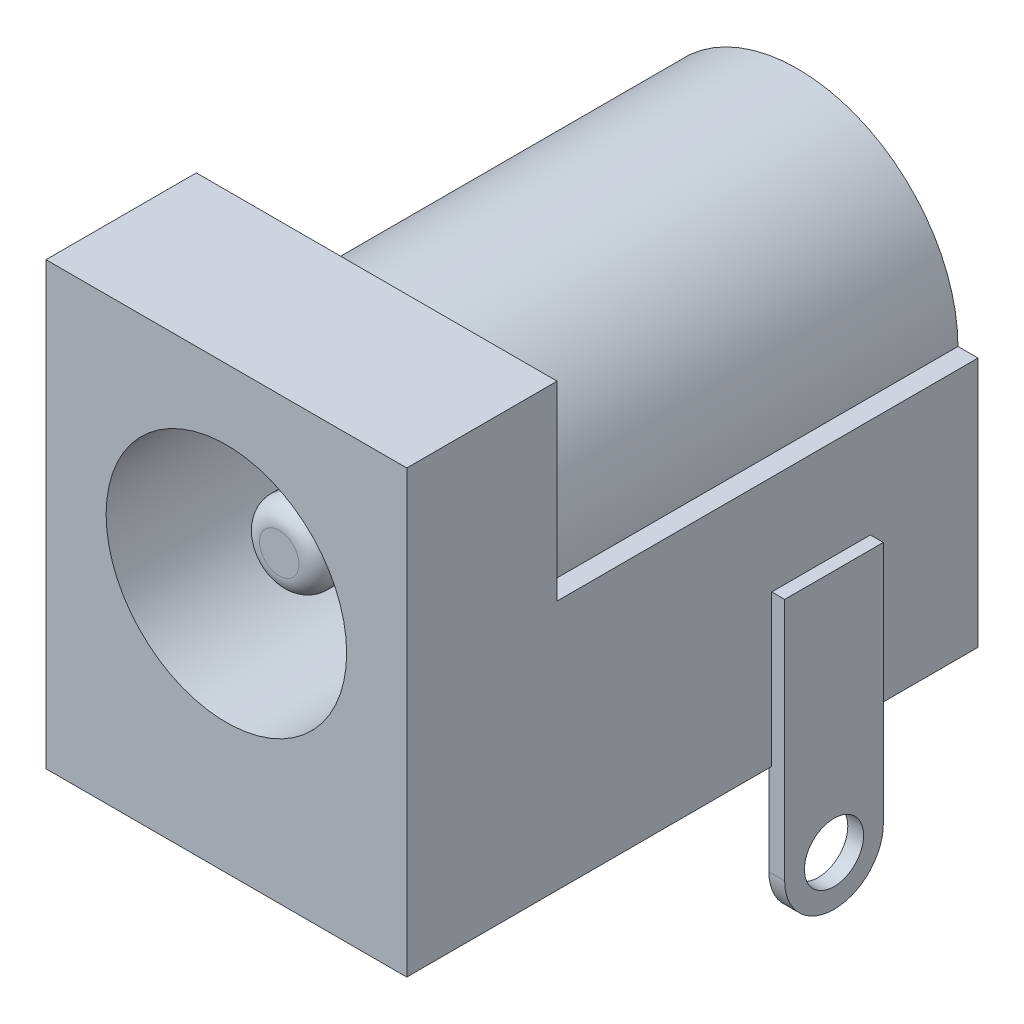
SolidWorks part; units mm, degrees
ref_plane "Plane1" through (0, 0, 0) normal (0, 0, 1) x (1, 0, 0)
ref_plane "Plane2" through (0, 0, 0) normal (0, 1, 0) x (1, 0, 0)
ref_plane "Plane3" through (0, 0, 0) normal (1, 0, 0) x (0, 0, -1)
sketch "Sketch1" plane through (0, 0, 0) normal (0, 0, 1) x (1, 0, 0)
  line L1 (-4.572, 0) -> (4.572, 0)
  line L2 (-4.572, 0) -> (-4.572, 11.176)
  line L3 (-4.572, 11.176) -> (4.572, 11.176)
  line L4 (4.572, 0) -> (4.572, 11.176)
  dimension "D1" = 9.144
  dimension "D2" = 11.176
extrude "Base-Extrude" add sketch "Sketch1" against normal blind 3.81
sketch "Sketch2" plane through (0, 0, -3.81) normal (0, 0, -1) x (-1, 0, 0)
  line L0 (4.572, 0) -> (-4.572, 0) construction
  line L1 (-4.572, 0) -> (-4.572, 11.176) construction
  line L2 (4.572, 11.176) -> (4.572, 0) construction
  line L3 (-4.572, 0) -> (-4.572, 6.35)
  line L4 (4.572, 0) -> (-4.572, 0)
  line L5 (4.572, 6.35) -> (4.572, 0)
  line L6 (-4.064, 6.35) -> (-4.572, 6.35)
  line L7 (4.064, 6.35) -> (4.572, 6.35)
  arc A0 (-4.064, 6.35) -> (4.064, 6.35) centre (0, 6.35) cw
  dimension "D1" = 4.064
  dimension "D2" = 6.35
extrude "Boss-Extrude1" add sketch "Sketch2" along normal blind 10.668
sketch "Sketch3" plane through (0, 0, 0) normal (0, 0, 1) x (1, 0, 0)
  circle A0 centre (0, 6.35) radius 3.048
  dimension "D1" = 6.096
extrude "Cut-Extrude1" cut sketch "Sketch3" against normal blind 9.144
sketch "Sketch4" plane through (0, 0, -9.144) normal (0, 0, 1) x (1, 0, 0)
  circle A0 centre (0, 6.35) radius 1
  dimension "D1" = 2
extrude "Extrude1" add sketch "Sketch4" along normal offset from surface (7.804 mm away) 1.34
fillet "Fillet1" radius 0.5
ref_plane "Plane4" through (4.7, 0, 0) normal (1, 0, 0) x (0, 0, -1)
sketch "Sketch5" plane through (4.7, 0, 0) normal (1, 0, 0) x (0, 0, -1)
  line L0 (11.75, 3.83) -> (11.75, -2.35)
  line L1 (9.25, 3.83) -> (9.25, -2.35)
  line L2 (9.25, 3.83) -> (11.75, 3.83)
  line L3 (14.478, 0) -> (0, 0) construction
  line L4 (0, 0) -> (0, 11.176) construction
  line L6 (14.478, 6.35) -> (3.81, 6.35) construction
  arc A0 (11.75, -2.35) -> (9.25, -2.35) centre (10.5, -2.35) cw
  circle A1 centre (10.5, -2.35) radius 0.75
  dimension "D2" = 3.6
  dimension "D5" = 1.5
  dimension "D1" = 2.5
  dimension "D3" = 10.5
  dimension "D4" = 2.52
extrude "Extrude2" add sketch "Sketch5" along normal mid plane 0.4
ref_plane "Plane5" through (0, 0, -7.5) normal (0, 0, 1) x (-1, 0, 0)
sketch "Sketch6" plane through (0, 0, -7.5) normal (0, 0, 1) x (-1, 0, 0)
  line L0 (0, 0) -> (0, 5.5847) construction
  line L1 (-1.1, 0) -> (-1.1, 2.5)
  line L2 (4.572, 0) -> (-4.572, 0) construction
  line L3 (1.1, 0) -> (1.1, 2.5)
  line L4 (1.1, 0) -> (-1.1, 0)
  arc A0 (1.1, 2.5) -> (-1.1, 2.5) centre (0, 2.5) ccw
  circle A1 centre (0, 2.5) radius 0.75
  dimension "D2" = 3.6
  dimension "D3" = 1.5
  dimension "D1" = 2.2
extrude "Extrude3" add sketch "Sketch6" along normal mid plane 0.3
ref_plane "Plane6" through (0, 0, -13.7) normal (0, 0, 1) x (1, 0, 0)
sketch "Sketch7" plane through (0, 0, -13.7) normal (0, 0, 1) x (1, 0, 0)
  line L0 (0, 0) -> (0, -4.6387) construction
  line L1 (1.425, 0) -> (1.425, -2.175)
  line L2 (4.572, 0) -> (-4.572, 0) construction
  line L3 (-1.425, 0) -> (-1.425, -2.175)
  line L4 (1.425, 0) -> (-1.425, 0)
  arc A0 (1.425, -2.175) -> (-1.425, -2.175) centre (0, -2.175) cw
  circle A3 centre (0, -2.175) radius 0.75
  dimension "D2" = 3.6
  dimension "D3" = 1.5
  dimension "D1" = 2.85
extrude "Extrude4" add sketch "Sketch7" along normal mid plane 0.4
